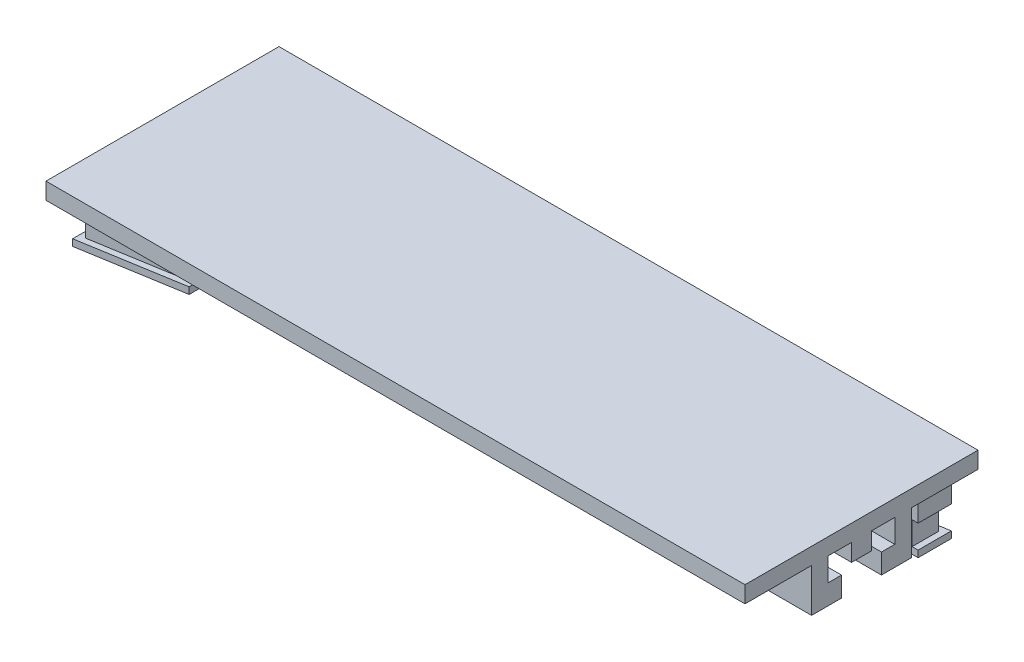
SolidWorks part; units mm, degrees
ref_plane "Front Plane" through (0, 0, 0) normal (0, 0, 1) x (1, 0, 0)
ref_plane "Top Plane" through (0, 0, 0) normal (0, 1, 0) x (1, 0, 0)
ref_plane "Right Plane" through (0, 0, 0) normal (1, 0, 0) x (0, 0, -1)
sketch "Sketch1" plane through (0, 0, 0) normal (1, 0, 0) x (0, 0, -1)
  line L0 (-35, -2.5) -> (-15, -2.5)
  line L2 (-35, -2.5) -> (-35, 2.5)
  line L3 (-35, 2.5) -> (35, 2.5)
  line L4 (35, -2.5) -> (35, 2.5)
  line L5 (-10, -2.5) -> (-10, -9.5)
  line L6 (-10, -2.5) -> (-3, -2.5)
  line L8 (-3, -2.5) -> (-3, -7.7101)
  line L9 (-3, -7.7101) -> (3, -7.7101)
  line L10 (3, -2.5) -> (3, -7.7101)
  line L12 (-15, -2.5) -> (-15, -15.5)
  line L15 (-10, -9.5) -> (-6, -9.5)
  line L18 (-6, -9.5) -> (-6, -15.5)
  line L22 (15, -2.5) -> (15, -15.5)
  line L23 (6, -9.5) -> (10, -9.5)
  line L24 (6, -9.5) -> (6, -15.5)
  line L26 (3, -2.5) -> (10, -2.5)
  line L27 (10, -2.5) -> (10, -9.5)
  line L28 (15, -2.5) -> (35, -2.5)
  line L29 (-15, -15.5) -> (-6, -15.5)
  line L30 (6, -15.5) -> (15, -15.5)
  point P0 (0, 0)
  point P22 (0, -7.7101)
  point P25 (0, 2.5)
  dimension "D1" = 70
  dimension "D2" = 5
  dimension "D3" = 6
  dimension "D4" = 0
  dimension "D5" = 0
  dimension "D6" = 7
  dimension "D7" = 7
  dimension "D8" = 7
  dimension "D9" = 7
  dimension "D10" = 4
  dimension "D11" = 6
  dimension "D12" = 4
  dimension "D13" = 6
  dimension "D14" = 9
  dimension "D15" = 9
extrude "Boss-Extrude1" add sketch "Sketch1" along normal blind 210 contours L0 L12 L29 L18 L15 L5 L6 L8 L9 L10 L26 L27 L23 L24 L30 L22 L28 L4 L3 L2
sketch "Sketch2" plane through (0, -2.5, 0) normal (0, -1, 0) x (1, 0, 0)
  line L0 (1, 28) -> (31, 23)
  line L1 (31, 23) -> (31, 18)
  line L2 (31, 18) -> (1, 18)
  line L3 (1, 18) -> (1, 28)
  line L4 (210, 15) -> (0, 15) construction
  line L5 (0, 35) -> (0, 15) construction
  line L6 (209, -18) -> (209, -28)
  line L7 (209, -18) -> (179, -18)
  line L8 (179, -18) -> (179, -23)
  line L9 (179, -23) -> (209, -28)
  line L10 (210, -15) -> (0, -15) construction
  line L11 (210, -15) -> (210, -35) construction
  dimension "D1" = 3
  dimension "D2" = 10
  dimension "D3" = 5
  dimension "D4" = 30
  dimension "D5" = 1
  dimension "D6" = 3
  dimension "D7" = 10
  dimension "D8" = 5
  dimension "D9" = 1
  dimension "D10" = 30
extrude "Boss-Extrude2" add sketch "Sketch2" along normal blind 15
sketch "Sketch3" plane through (1, 0, 0) normal (-1, 0, 0) x (0, 0, 1)
  line L0 (18, -17.5) -> (18, -2.5) construction
  line L1 (18, -15.5) -> (28, -15.5)
  line L2 (28, -17.5) -> (28, -2.5) construction
  line L3 (28, -15.5) -> (28, -8.5)
  line L4 (28, -8.5) -> (18, -8.5)
  line L5 (18, -8.5) -> (18, -15.5)
  line L6 (28, -17.5) -> (18, -17.5) construction
  dimension "D1" = 2
  dimension "D2" = 7
extrude "Cut-Extrude1" cut sketch "Sketch3" against normal blind 1.8
sketch "Sketch5" plane through (209, 0, 0) normal (1, 0, 0) x (0, 0, -1)
  line L0 (18, -8.5) -> (28, -8.5)
  line L1 (18, -17.5) -> (18, -2.5) construction
  line L2 (28, -17.5) -> (28, -2.5) construction
  line L3 (28, -8.5) -> (28, -15.5)
  line L4 (28, -15.5) -> (18, -15.5)
  line L5 (18, -15.5) -> (18, -8.5)
  line L6 (28, -17.5) -> (18, -17.5) construction
  dimension "D1" = 2
  dimension "D2" = 7
extrude "Cut-Extrude2" cut sketch "Sketch5" against normal blind 1.8
sketch "Sketch7" plane through (0, -8.5, 0) normal (0, -1, 0) x (1, 0, 0)
  line L0 (207.2, -27.7) -> (179, -23)
  line L1 (179, -23) -> (209, -28) construction
  line L2 (179, -23) -> (179, -21.2)
  line L3 (179, -18) -> (179, -23) construction
  line L4 (179, -21.2) -> (207.2, -25.9)
  line L5 (207.2, -25.9) -> (207.2, -27.7)
  line L6 (209, -28) -> (209, -18) construction
  dimension "D1" = 1.8
  dimension "D2" = 1.8
extrude "Cut-Extrude3" cut sketch "Sketch7" along normal blind 7
sketch "Sketch8" plane through (0, -8.5, 0) normal (0, -1, 0) x (1, 0, 0)
  line L0 (2.8, 27.7) -> (31, 23)
  line L1 (31, 23) -> (1, 28) construction
  line L2 (31, 23) -> (31, 21.2)
  line L3 (31, 18) -> (31, 23) construction
  line L4 (31, 21.2) -> (2.8, 25.9)
  line L5 (2.8, 25.9) -> (2.8, 27.7)
  line L6 (1, 28) -> (1, 18) construction
  dimension "D1" = 1.8
  dimension "D2" = 1.8
extrude "Cut-Extrude4" cut sketch "Sketch8" along normal blind 7
